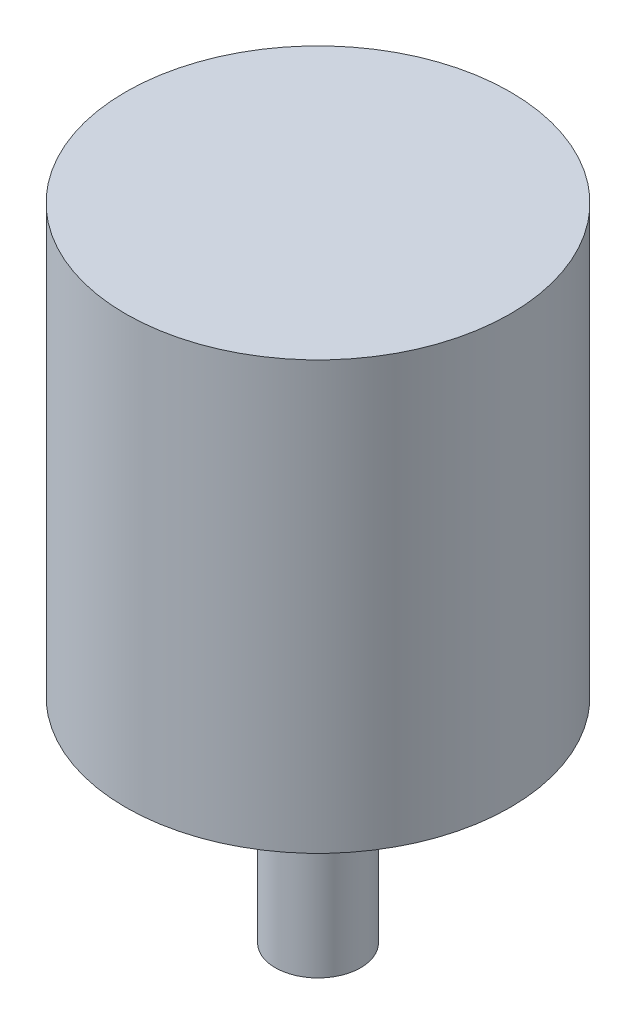
SolidWorks part; units mm, degrees
ref_plane "Front Plane" through (0, 0, 0) normal (0, 0, 1) x (1, 0, 0)
ref_plane "Top Plane" through (0, 0, 0) normal (0, 1, 0) x (1, 0, 0)
ref_plane "Right Plane" through (0, 0, 0) normal (1, 0, 0) x (0, 0, -1)
sketch "Sketch1" plane through (0, 0, 0) normal (0, 1, 0) x (1, 0, 0)
  circle A0 centre (0, 0) radius 18
extrude "Boss-Extrude1" add sketch "Sketch1" along normal blind 40
sketch "Sketch2" plane through (0, 0, 0) normal (0, -1, 0) x (1, 0, 0)
  circle A1 centre (-15, 0) radius 1.5
extrude "Cut-Extrude1" cut sketch "Sketch2" against normal blind 5
pattern_circular "CirPattern1" count 4 over 360 about axis through (0, 0, 0) along (0, 1, 0) of "Cut-Extrude1"
sketch "Sketch3" plane through (0, 0, 0) normal (0, -1, 0) x (1, 0, 0)
  circle A0 centre (0, 0) radius 11
extrude "Boss-Extrude2" add sketch "Sketch3" along normal blind 3
sketch "Sketch4" plane through (0, -3, 0) normal (0, -1, 0) x (1, 0, 0)
  circle A0 centre (0, 0) radius 4
extrude "Boss-Extrude3" add sketch "Sketch4" along normal blind 17
sketch "Sketch5" plane through (0, -20, 0) normal (0, -1, 0) x (1, 0, 0)
  line L0 (-2.6458, -3) -> (2.6458, -3)
  arc A4 (2.6458, -3) -> (-2.6458, -3) centre (0, 0) cw
  point P7 (0, -3)
extrude "Cut-Extrude2" cut sketch "Sketch5" against normal blind 15
